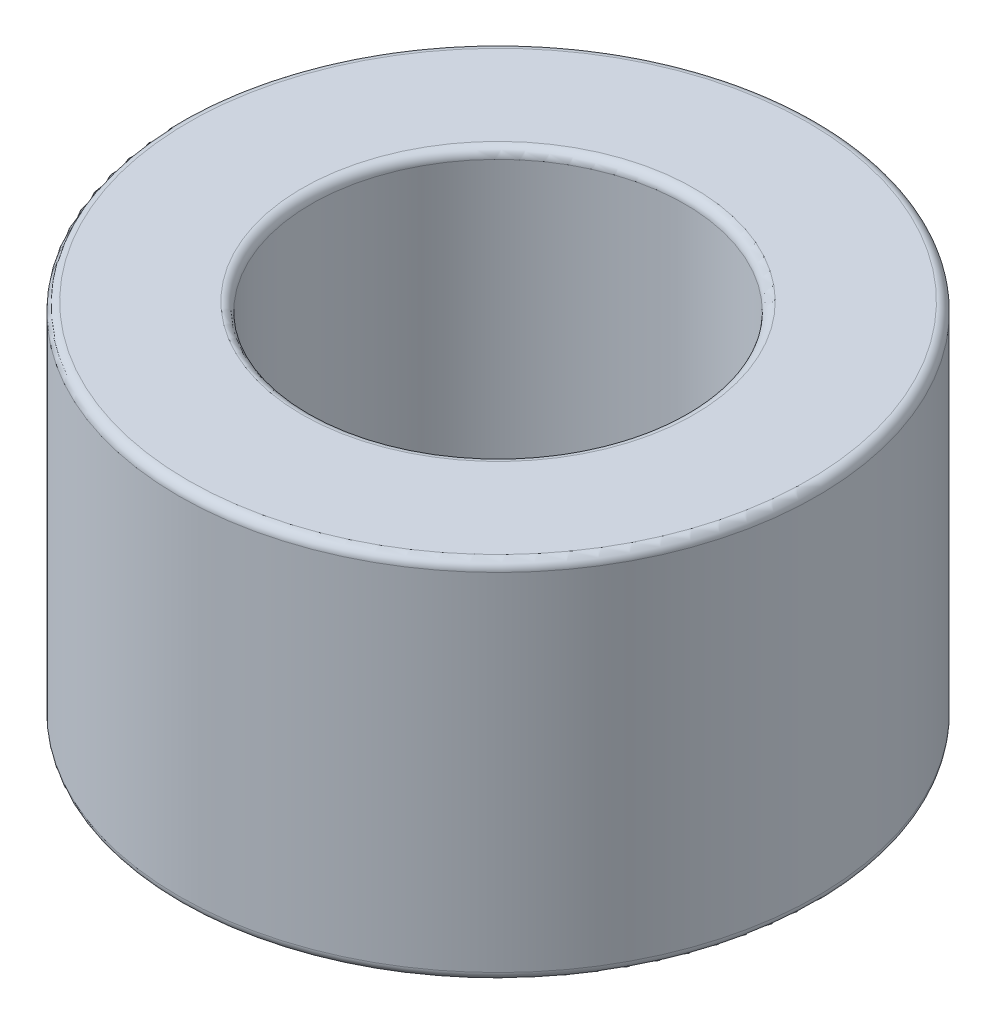
SolidWorks part; units mm, degrees
material "6061-T6 (SS)"
ref_plane "Front Plane" through (0, 0, 0) normal (0, 0, 1) x (1, 0, 0)
ref_plane "Top Plane" through (0, 0, 0) normal (0, 1, 0) x (1, 0, 0)
ref_plane "Right Plane" through (0, 0, 0) normal (1, 0, 0) x (0, 0, -1)
sketch "Sketch1" plane through (0, 0, 0) normal (0, 1, 0) x (1, 0, 0)
  circle A0 centre (0, 0) radius 2.05
  circle A1 centre (0, 0) radius 3.5
  dimension "D1" = 4.1
  dimension "D2" = 7
extrude "Boss-Extrude1" add sketch "Sketch1" along normal blind 4
fillet "Fillet1" radius 0.1 3 edges at (0, 4, 2.05) (0, 0, 3.5) (0, 4, 3.5)
